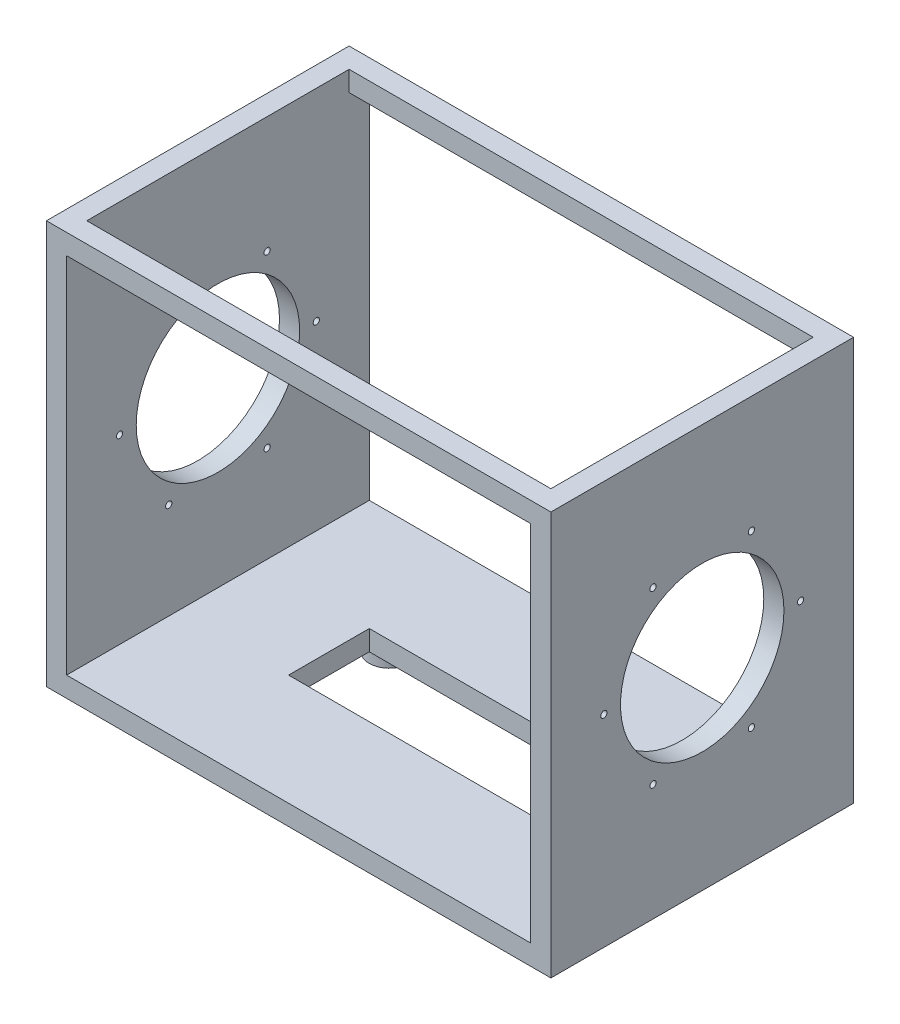
SolidWorks part; units mm, degrees
ref_plane "前视基准面" through (0, 0, 0) normal (0, 0, 1) x (1, 0, 0)
ref_plane "上视基准面" through (0, 0, 0) normal (0, 1, 0) x (1, 0, 0)
ref_plane "右视基准面" through (0, 0, 0) normal (1, 0, 0) x (0, 0, -1)
other "Configuration Table"
sketch "草图1" plane through (0, 0, 0) normal (0, 1, 0) x (1, 0, 0)
  line L1 (-125, -75) -> (125, -75)
  line L2 (-125, -75) -> (-125, 75)
  line L3 (-125, 75) -> (125, 75)
  line L4 (125, -75) -> (125, 75)
  line L5 (-125, -75) -> (125, 75) construction
  line L6 (-125, 75) -> (125, -75) construction
  point P0 (0, 0)
  dimension "D1" = 250
  dimension "D2" = 150
extrude "凸台-拉伸2" add sketch "草图1" along normal blind 200
sketch "草图3" plane through (0, 200, 0) normal (0, 1, 0) x (1, 0, 0)
  line L1 (-115, -65) -> (115, -65)
  line L2 (-115, -65) -> (-115, 65)
  line L3 (-115, 65) -> (115, 65)
  line L4 (115, -65) -> (115, 65)
  line L5 (-115, -65) -> (115, 65) construction
  line L6 (-115, 65) -> (115, -65) construction
  point P0 (0, 0)
  dimension "D1" = 230
  dimension "D2" = 130
extrude "切除-拉伸1" cut sketch "草图3" against normal blind 190
sketch "草图4" plane through (0, 0, 75) normal (0, 0, 1) x (1, 0, 0)
  line L6 (-115, 10) -> (115, 10)
  line L7 (-115, 10) -> (-115, 190)
  line L8 (-115, 190) -> (115, 190)
  line L9 (115, 10) -> (115, 190)
  line L10 (-115, 10) -> (115, 190) construction
  line L11 (-115, 190) -> (115, 10) construction
  point P12 (0, 100)
  dimension "D1" = 180
  dimension "D2" = 230
extrude "切除-拉伸2" cut sketch "草图4" against normal blind 190
sketch "草图5" plane through (125, 0, 0) normal (1, 0, 0) x (0, 0, -1)
  line L0 (0, 100) -> (0, 200)
  line L11 (-75, 200) -> (75, 200) construction
  circle A0 centre (0, 100) radius 40.5
  circle A2 centre (-24.375, 142.2187) radius 1.55
  circle A4 centre (-48.75, 100) radius 1.55
  circle A5 centre (24.375, 142.2187) radius 1.55
  circle A6 centre (48.75, 100) radius 1.55
  circle A7 centre (24.375, 57.7813) radius 1.55
  circle A8 centre (-24.375, 57.7813) radius 1.55
  point P16 (0, 100)
  dimension "D1" = 3.1
extrude "切除-拉伸3" cut sketch "草图5" against normal blind 250
sketch "草图6" plane through (0, 0, 0) normal (0, -1, 0) x (1, 0, 0)
  line L5 (-75, -45) -> (75, 45) construction
  line L6 (-75, 45) -> (75, -45) construction
  circle A0 centre (-75, 45) radius 10
  circle A1 centre (-75, -45) radius 10
  circle A2 centre (75, 45) radius 10
  circle A3 centre (75, -45) radius 10
  point P0 (0, 0)
  point P7 (-75, 45)
  point P8 (75, 45)
  point P9 (75, -45)
  point P10 (-75, -45)
  dimension "D1" = 150
  dimension "D2" = 90
ref_plane "基准面3" through (0, 0, 45) normal (0, 0, 1) x (1, 0, 0)
sketch "草图10" plane through (0, 0, 45) normal (0, 0, 1) x (1, 0, 0)
  line L0 (-75, 0) -> (-75, -20)
  line L1 (-75, -20) -> (-85, -20)
  line L2 (-85, -20) -> (-85, -10)
  line L4 (-85, 0) -> (-65, 0) construction
  line L5 (-125, 0) -> (125, 0) construction
  line L6 (-85, 0) -> (-95, 0)
  line L7 (-95, 0) -> (-85, -10)
  line L8 (-85, 0) -> (-75, 0)
revolve "旋转2" add sketch "草图10" angle 360 about L0
ref_plane "基准面4" through (0, 0, 45) normal (0, 0, 1) x (1, 0, 0)
sketch "草图11" plane through (0, 0, 45) normal (0, 0, 1) x (1, 0, 0)
  line L0 (75, 0) -> (55, 0)
  line L1 (-75, 0) -> (75, 0) construction
  line L2 (75, 0) -> (75, -20)
  line L3 (75, -20) -> (65, -20)
  line L4 (65, -20) -> (65, -10)
  line L5 (65, -10) -> (55, 0)
revolve "旋转4" add sketch "草图11" angle 360 about L2
ref_plane "基准面5" through (0, 0, -45) normal (0, 0, -1) x (-1, 0, 0)
sketch "草图12" plane through (0, 0, -45) normal (0, 0, -1) x (-1, 0, 0)
  line L0 (-75, 0) -> (-55, 0)
  line L1 (-75, 0) -> (-75, -20)
  line L2 (-75, -20) -> (-65, -20)
  line L3 (-65, -20) -> (-65, -10)
  line L4 (-65, -10) -> (-55, 0)
revolve "旋转5" add sketch "草图12" angle 360 about L1
ref_plane "基准面6" through (0, 0, -45) normal (0, 0, -1) x (-1, 0, 0)
sketch "草图13" plane through (0, 0, -45) normal (0, 0, -1) x (-1, 0, 0)
  line L0 (75, 0) -> (55, 0)
  line L1 (75, 0) -> (75, -20)
  line L2 (65, -20) -> (85, -20) construction
  line L3 (75, -20) -> (65, -20)
  line L4 (65, -20) -> (65, -10)
  line L5 (65, -10) -> (85, -10) construction
  line L6 (65, -10) -> (55, 0)
revolve "旋转6" add sketch "草图13" angle 360 about L1
sketch "草图14" plane through (0, 10, 0) normal (0, 1, 0) x (1, 0, 0)
  line L1 (-60, -20) -> (60, -20)
  line L2 (-60, -20) -> (-60, 20)
  line L3 (-60, 20) -> (60, 20)
  line L4 (60, -20) -> (60, 20)
  line L5 (-60, -20) -> (60, 20) construction
  line L6 (-60, 20) -> (60, -20) construction
  point P0 (0, 0)
  dimension "D1" = 40
  dimension "D2" = 120
extrude "切除-拉伸4" cut sketch "草图14" against normal blind 20
